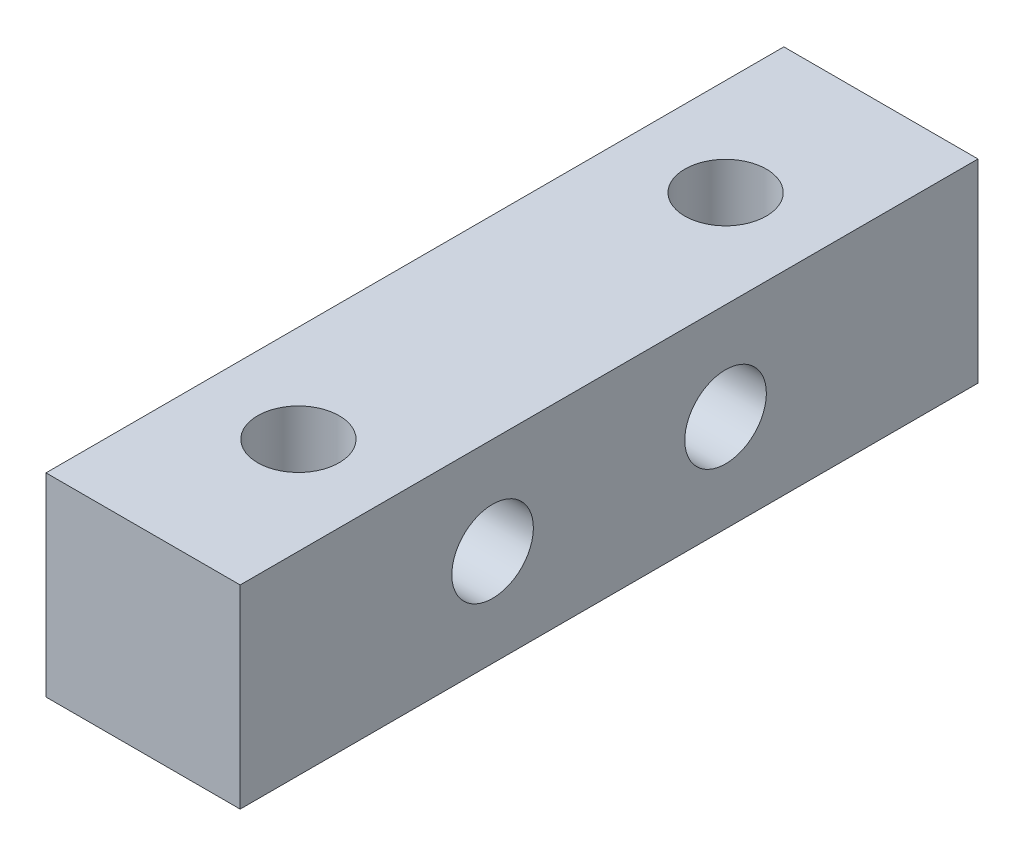
SolidWorks part; units mm, degrees
ref_plane "前视基准面" through (0, 0, 0) normal (0, 0, 1) x (1, 0, 0)
ref_plane "上视基准面" through (0, 0, 0) normal (0, 1, 0) x (1, 0, 0)
ref_plane "右视基准面" through (0, 0, 0) normal (1, 0, 0) x (0, 0, -1)
sketch "草图1" plane through (0, 0, 0) normal (0, 0, 1) x (1, 0, 0)
  line L1 (0, 10) -> (10, 10)
  line L2 (0, 10) -> (0, 0)
  line L3 (0, 0) -> (10, 0)
  line L4 (10, 10) -> (10, 0)
  point P4 (0, 0)
  dimension "D1" = 10
  dimension "D2" = 10
extrude "凸台-拉伸1" add sketch "草图1" along normal blind 38
sketch "草图3" plane through (0, 10, 0) normal (0, 1, 0) x (1, 0, 0)
  line L0 (5, 0) -> (5, -38)
  line L1 (10, 0) -> (0, 0) construction
  line L2 (10, -38) -> (0, -38) construction
  circle A2 centre (5, -8) radius 2.1
  circle A4 centre (5, -30) radius 2.1
  point P10 (5, 0)
  dimension "D1" = 8
  dimension "D2" = 22
  dimension "D3" = 4.2
  dimension "D4" = 4.2
extrude "切除-拉伸1" cut sketch "草图3" against normal blind 22 contours L0 A2 | L0 A2 | L0 A4 | L0 A4
sketch "草图4" plane through (10, 0, 0) normal (1, 0, 0) x (0, 0, -1)
  line L0 (-38, 5) -> (0, 5) construction
  line L1 (-38, 0) -> (-38, 10) construction
  line L2 (0, 0) -> (0, 10) construction
  circle A0 centre (-25, 5) radius 2.1
  circle A1 centre (-13, 5) radius 2.1
  dimension "D1" = 13
  dimension "D2" = 12
  dimension "D3" = 4.2
  dimension "D4" = 4.2
extrude "切除-拉伸2" cut sketch "草图4" against normal blind 22
